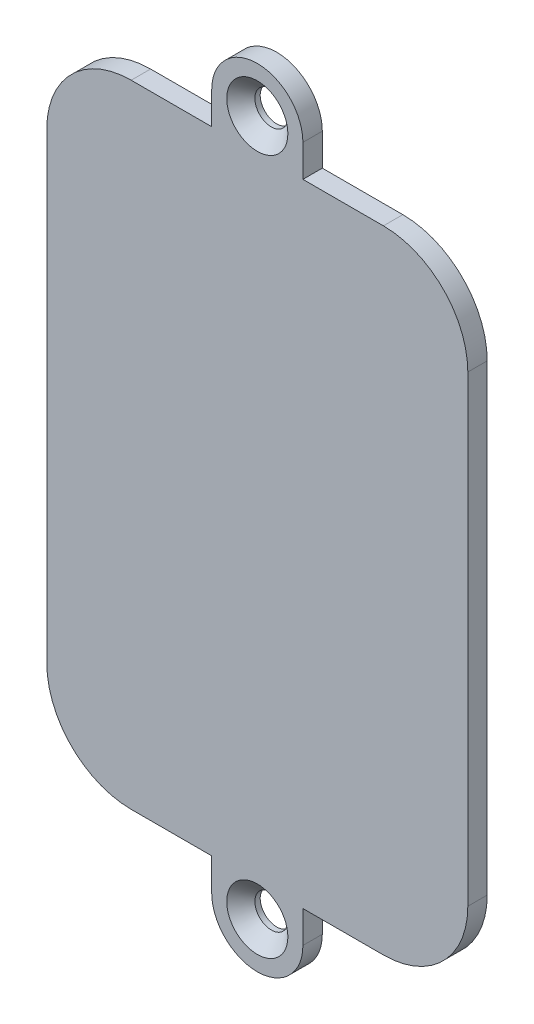
SolidWorks part; units mm, degrees
ref_plane "Plan de face" through (0, 0, 0) normal (0, 0, 1) x (1, 0, 0)
ref_plane "Plan de dessus" through (0, 0, 0) normal (0, 1, 0) x (1, 0, 0)
ref_plane "Plan de droite" through (0, 0, 0) normal (1, 0, 0) x (0, 0, -1)
sketch "Esquisse1" plane through (0, 0, 0) normal (0, 0, 1) x (1, 0, 0)
  line L20 (-4.7, 69.04) -> (-4.7, 65.74)
  line L21 (-4.7, 65.74) -> (-13, 65.74)
  line L22 (-21.7, 57.04) -> (-21.7, 9.35)
  line L23 (-13, 0.65) -> (-4.7, 0.65)
  line L24 (-4.7, 0.65) -> (-4.7, -2.65)
  line L25 (4.7, -2.65) -> (4.7, 0.65)
  line L26 (4.7, 0.65) -> (13, 0.65)
  line L27 (21.7, 9.35) -> (21.7, 57.04)
  line L28 (13, 65.74) -> (4.7, 65.74)
  line L29 (4.7, 65.74) -> (4.7, 69.04)
  line L30 (-4.7, 69.04) -> (-4.7, 65.74)
  line L31 (-4.7, 65.74) -> (-13, 65.74)
  line L32 (-21.7, 57.04) -> (-21.7, 9.35)
  line L33 (-13, 0.65) -> (-4.7, 0.65)
  line L34 (-4.7, 0.65) -> (-4.7, -2.65)
  line L35 (4.7, -2.65) -> (4.7, 0.65)
  line L36 (4.7, 0.65) -> (13, 0.65)
  line L37 (21.7, 9.35) -> (21.7, 57.04)
  line L38 (13, 65.74) -> (4.7, 65.74)
  line L39 (4.7, 65.74) -> (4.7, 69.04)
  arc A12 (-13, 65.74) -> (-21.7, 57.04) centre (-13, 57.04) ccw
  arc A13 (-21.7, 9.35) -> (-13, 0.65) centre (-13, 9.35) ccw
  arc A14 (-4.7, -2.65) -> (4.7, -2.65) centre (0, -2.65) ccw
  arc A15 (13, 0.65) -> (21.7, 9.35) centre (13, 9.35) ccw
  arc A16 (21.7, 57.04) -> (13, 65.74) centre (13, 57.04) ccw
  arc A17 (4.7, 69.04) -> (-4.7, 69.04) centre (0, 69.04) ccw
  arc A18 (-13, 65.74) -> (-21.7, 57.04) centre (-13, 57.04) ccw
  arc A19 (-21.7, 9.35) -> (-13, 0.65) centre (-13, 9.35) ccw
  arc A20 (-4.7, -2.65) -> (4.7, -2.65) centre (0, -2.65) ccw
  arc A21 (13, 0.65) -> (21.7, 9.35) centre (13, 9.35) ccw
  arc A22 (21.7, 57.04) -> (13, 65.74) centre (13, 57.04) ccw
  arc A23 (4.7, 69.04) -> (-4.7, 69.04) centre (0, 69.04) ccw
  dimension "D1" = 0.3
extrude "Boss.-Extru.1" add sketch "Esquisse1" along normal blind 2
hole_wizard "Fraisage pour vis à tête fraisée M31" positions "Esquisse2" profile "Esquisse4" countersink size "M3" standard "ISO" end condition up to next
sketch "Esquisse2" plane through (0, 0, 2) normal (0, 0, 1) x (1, 0, 0)
  point P0 (0, 69.04)
  point P3 (0, -2.65)
sketch "Esquisse4" plane through (0, 69.04, 2) normal (1, 0, 0) x (0, -1, 0)
  line L0 (0, 0) -> (0, 2)
  line L1 (0, 2) -> (1.7, 2)
  line L2 (1.7, 2) -> (1.7, 1.45)
  line L3 (1.7, 1.45) -> (3.15, 0)
  line L5 (3.15, 0) -> (0, 0)
  line L6 (-1.7, 1.45) -> (-3.15, 0) construction
  line L11 (0, -6.35) -> (0, 107.95) construction
  dimension "Diamètre du perçage jusqu'au prochain" = 3.4
  dimension "Profondeur du perçage jusqu'au prochain" = 2
  dimension "Diamètre du fraisage entrant" = 6.3
  dimension "Angle du fraisage entrant" = 90
